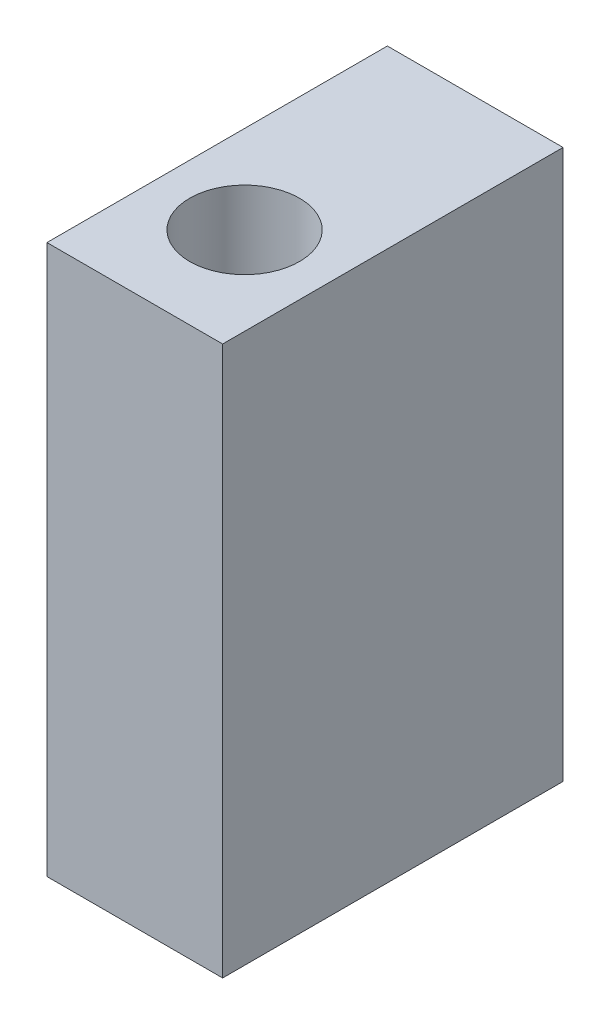
SolidWorks part; units mm, degrees
material "Galvanized Steel"
ref_plane "Front Plane" through (0, 0, 0) normal (0, 0, 1) x (1, 0, 0)
ref_plane "Top Plane" through (0, 0, 0) normal (0, 1, 0) x (1, 0, 0)
ref_plane "Right Plane" through (0, 0, 0) normal (1, 0, 0) x (0, 0, -1)
sketch "Sketch1" plane through (0, 0, 0) normal (0, 1, 0) x (1, 0, 0)
  line L1 (8, -15.5) -> (-8, -15.5)
  line L2 (8, -15.5) -> (8, 15.5)
  line L3 (8, 15.5) -> (-8, 15.5)
  line L4 (-8, -15.5) -> (-8, 15.5)
  line L5 (8, -15.5) -> (-8, 15.5) construction
  line L6 (8, 15.5) -> (-8, -15.5) construction
  point P0 (0, 0)
  dimension "D1" = 16
  dimension "D2" = 31
extrude "Boss-Extrude1" add sketch "Sketch1" along normal blind 50
sketch "Sketch2" plane through (0, 50, 0) normal (0, 1, 0) x (1, 0, 0)
  line L0 (-8, -15.5) -> (8, -15.5) construction
  circle A0 centre (0, -5.5) radius 5
  dimension "D1" = 10
  dimension "D2" = 10
extrude "Cut-Extrude1" cut sketch "Sketch2" against normal through all
